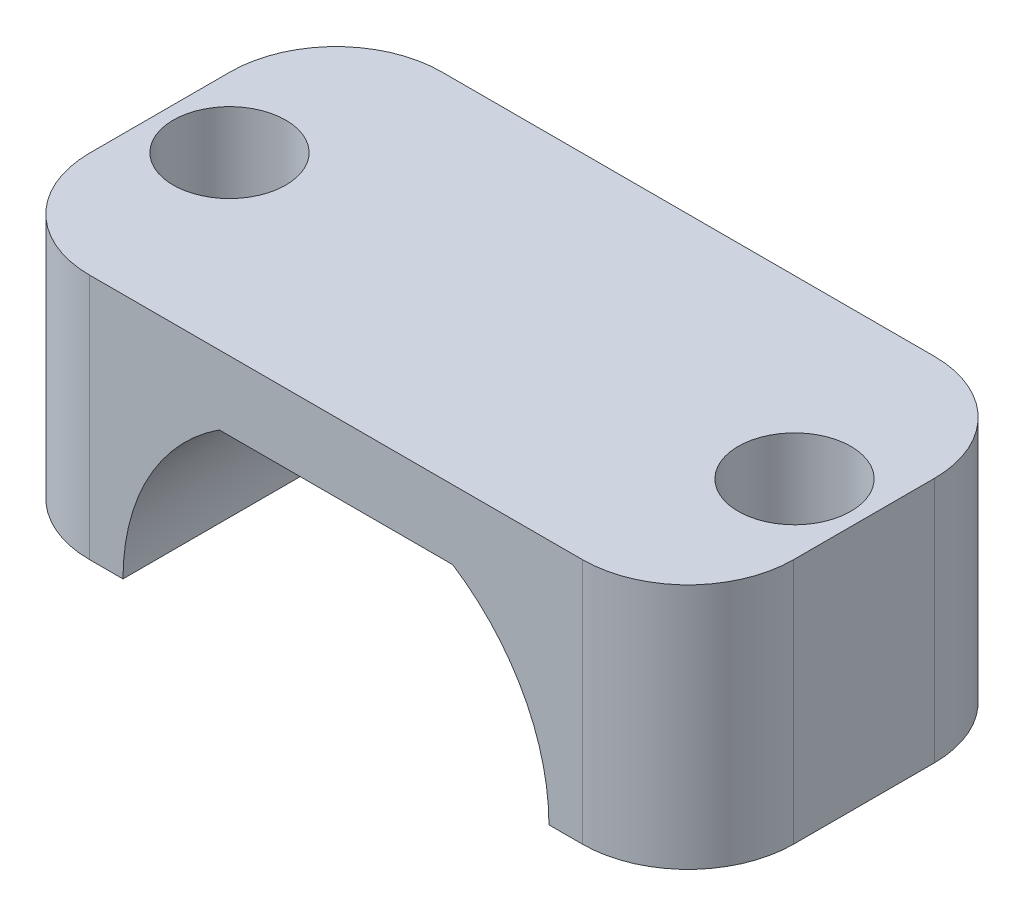
SolidWorks part; units mm, degrees
ref_plane "Front Plane" through (0, 0, 0) normal (0, 0, 1) x (1, 0, 0)
ref_plane "Top Plane" through (0, 0, 0) normal (0, 1, 0) x (1, 0, 0)
ref_plane "Right Plane" through (0, 0, 0) normal (1, 0, 0) x (0, 0, -1)
sketch "Sketch1" plane through (0, 0, 0) normal (0, 0, 1) x (1, 0, 0)
  line L0 (-10, 0) -> (10, 0)
  line L1 (10, 0) -> (10, -7)
  line L2 (10, -7) -> (6.05, -7)
  line L3 (3.315, -1.9661) -> (-3.315, -1.9661)
  line L4 (-6.05, -7) -> (-10, -7)
  line L5 (-10, -7) -> (-10, 0)
  arc A0 (6.05, -7) -> (3.315, -1.9661) centre (0.05, -7) ccw
  arc A1 (-3.315, -1.9661) -> (-6.05, -7) centre (-0.05, -7) ccw
  point P3 (1.0451, -17.6216)
  point P4 (0, 0)
  point P12 (0, -1.9661)
  point P14 (0, 0)
  dimension "D1" = 6
  dimension "D2" = 6.63
  dimension "D3" = 20
  dimension "D4" = 12.1
  dimension "D5" = 7
extrude "Boss-Extrude1" add sketch "Sketch1" along normal mid plane 10
sketch "Sketch2" plane through (0, -7, 0) normal (0, -1, 0) x (1, 0, 0)
  line L0 (6.05, 5) -> (10, 5) construction
  line L1 (-10, 5) -> (-6.05, 5) construction
  circle A0 centre (8.025, 0) radius 1.6
  circle A1 centre (-8.025, 0) radius 1.6
  point P4 (0, 0)
  point P5 (0, 0)
  point P7 (0, 0)
  point P10 (8.025, 5)
  point P11 (0, 0)
  point P14 (-8.025, 5)
  dimension "D1" = 3.2
extrude "Cut-Extrude1" cut sketch "Sketch2" against normal through all
fillet "Fillet3" radius 3 4 edges at (10, -3.5, -5) (10, -3.5, 5) (-10, -3.5, -5) (-10, -3.5, 5)
